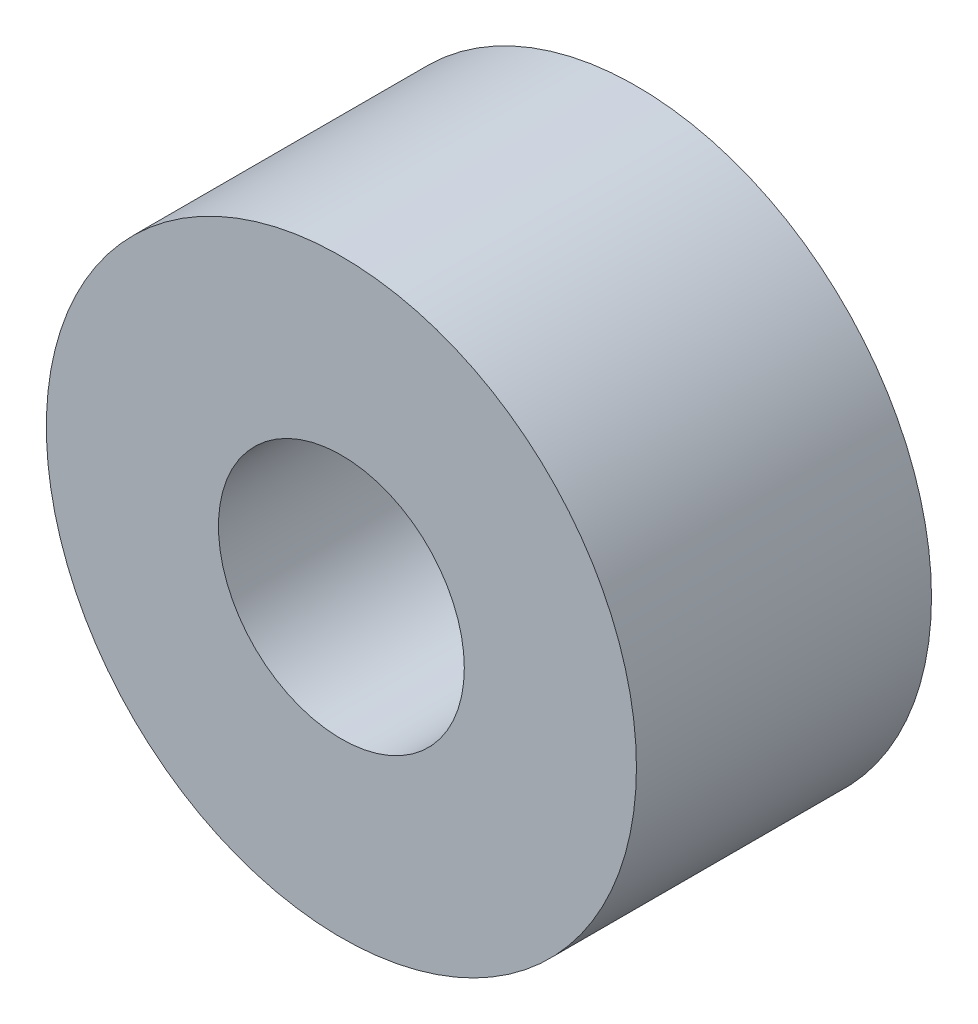
SolidWorks part; units mm, degrees
ref_plane "Front Plane" through (0, 0, 0) normal (0, 0, 1) x (1, 0, 0)
ref_plane "Top Plane" through (0, 0, 0) normal (0, 1, 0) x (1, 0, 0)
ref_plane "Right Plane" through (0, 0, 0) normal (1, 0, 0) x (0, 0, -1)
sketch "Sketch1" plane through (0, 0, 0) normal (0, 0, 1) x (1, 0, 0)
  circle A0 centre (0, 0) radius 1.25
  circle A1 centre (0, 0) radius 3
  dimension "D1" = 2.5
  dimension "D2" = 6
extrude "Boss-Extrude1" add sketch "Sketch1" along normal blind 3
